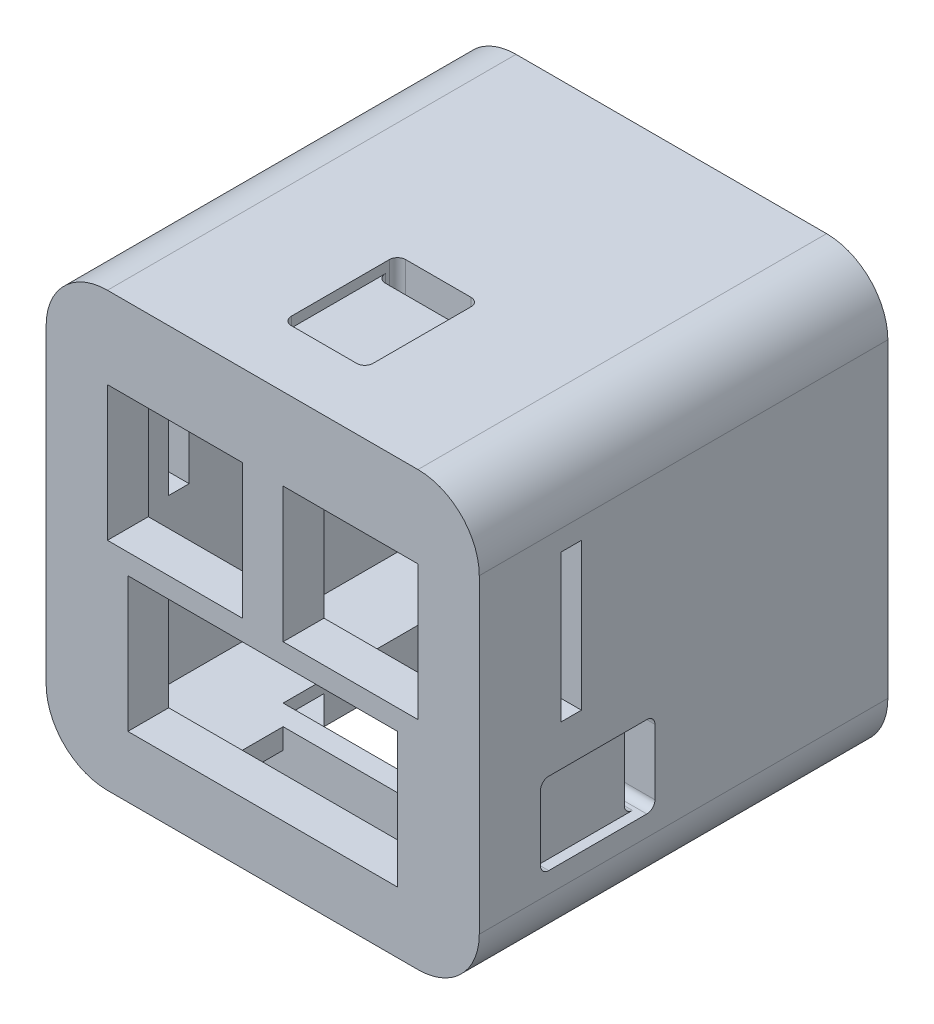
SolidWorks part; units mm, degrees
ref_plane "Front Plane" through (0, 0, 0) normal (0, 0, 1) x (1, 0, 0)
ref_plane "Top Plane" through (0, 0, 0) normal (0, 1, 0) x (1, 0, 0)
ref_plane "Right Plane" through (0, 0, 0) normal (1, 0, 0) x (0, 0, -1)
sketch "Sketch1" plane through (0, 0, 0) normal (0, 0, 1) x (1, 0, 0)
  line L1 (15, 0) -> (91, 0)
  line L2 (0, 15) -> (0, 91)
  line L3 (15, 106) -> (91, 106)
  line L4 (106, 15) -> (106, 91)
  line L5 (20, 15) -> (86, 15)
  line L6 (20, 15) -> (20, 48)
  line L7 (20, 48) -> (86, 48)
  line L8 (86, 15) -> (86, 48)
  line L9 (15, 86) -> (48, 86)
  line L10 (15, 86) -> (15, 53)
  line L11 (15, 53) -> (48, 53)
  line L12 (48, 86) -> (48, 53)
  line L13 (15, 86) -> (48, 53) construction
  line L14 (15, 53) -> (48, 86) construction
  line L19 (58, 86) -> (91, 86)
  line L20 (58, 86) -> (58, 53)
  line L21 (58, 53) -> (91, 53)
  line L22 (91, 86) -> (91, 53)
  line L23 (58, 86) -> (91, 53) construction
  line L24 (58, 53) -> (91, 86) construction
  arc A0 (91, 0) -> (106, 15) centre (91, 15) ccw
  arc A1 (0, 15) -> (15, 0) centre (15, 15) ccw
  arc A2 (15, 106) -> (0, 91) centre (15, 91) ccw
  arc A3 (91, 106) -> (106, 91) centre (91, 91) cw
  point P13 (106, 0)
  point P16 (0, 0)
  point P19 (0, 106)
  point P23 (87.3237, 87.1447)
  point P29 (31.5, 69.5)
  point P30 (74.5, 69.5)
  point P31 (0, 0)
  point P32 (53, 48)
  point P33 (53, 106)
  dimension "D7" = 15
  dimension "D1" = 66
  dimension "D2" = 33
  dimension "D3" = 10
  dimension "D4" = 5
  dimension "D5" = 33
  dimension "D6" = 33
  dimension "D8" = 33
  dimension "D9" = 33
  dimension "D10" = 15
  dimension "D11" = 15
  dimension "D12" = 20
  dimension "D13" = 15
extrude "Boss-Extrude1" add sketch "Sketch1" against normal blind 100
sketch "Sketch3" plane through (0, 0, -100) normal (0, 0, -1) x (-1, 0, 0)
  line L8 (-91, 106) -> (-15, 106) construction
  line L9 (-96, 96) -> (-10, 96)
  line L10 (-96, 96) -> (-96, 10)
  line L11 (-96, 10) -> (-10, 10)
  line L12 (-10, 96) -> (-10, 10)
  line L13 (-96, 96) -> (-10, 10) construction
  line L14 (-96, 10) -> (-10, 96) construction
  line L15 (0, 91) -> (0, 15) construction
  line L16 (-106, 15) -> (-106, 91) construction
  line L17 (-15, 0) -> (-91, 0) construction
  point P6 (-53, 53)
  dimension "D1" = 10
  dimension "D2" = 10
  dimension "D3" = 10
  dimension "D4" = 10
extrude "Cut-Extrude1" cut sketch "Sketch3" against normal offset from surface (90 mm away) 10 up to face at (31.5, 69.5, 0)
sketch "Sketch4" plane through (0, 106, 0) normal (0, 1, 0) x (1, 0, 0)
  line L0 (91, 100) -> (91, 0) construction
  line L1 (45, 43) -> (61, 43)
  line L2 (43, 41) -> (43, 17)
  line L3 (45, 15) -> (61, 15)
  line L4 (63, 41) -> (63, 17)
  line L5 (43, 43) -> (63, 15) construction
  line L6 (43, 15) -> (63, 43) construction
  line L8 (91, 0) -> (15, 0) construction
  arc A0 (63, 41) -> (61, 43) centre (61, 41) ccw
  arc A1 (63, 17) -> (61, 15) centre (61, 17) cw
  arc A2 (43, 17) -> (45, 15) centre (45, 17) ccw
  arc A3 (43, 41) -> (45, 43) centre (45, 41) cw
  point P4 (53, 29)
  dimension "D5" = 2
  dimension "D1" = 28
  dimension "D2" = 20
  dimension "D3" = 28
  dimension "D4" = 15
extrude "Cut-Extrude2" cut sketch "Sketch4" against normal blind 2.5
sketch "Sketch5" plane through (0, 103.5, 0) normal (0, 1, 0) x (1, 0, 0)
  line L0 (43, 41) -> (43, 17) construction
  line L1 (45, 38) -> (61, 38)
  line L2 (43, 40) -> (43, 41)
  line L3 (45, 43) -> (61, 43)
  line L4 (63, 40) -> (63, 41)
  line L5 (43, 38) -> (63, 43) construction
  line L6 (43, 43) -> (63, 38) construction
  line L8 (63, 17) -> (63, 41) construction
  line L9 (61, 43) -> (45, 43) construction
  arc A0 (61, 43) -> (63, 41) centre (61, 41) cw
  arc A1 (63, 40) -> (61, 38) centre (61, 40) cw
  arc A2 (43, 40) -> (45, 38) centre (45, 40) ccw
  arc A3 (43, 41) -> (45, 43) centre (45, 41) cw
  point P4 (53, 40.5)
  dimension "D2" = 2
  dimension "D1" = 5
extrude "Cut-Extrude3" cut sketch "Sketch5" against normal blind 18.5
ref_plane "Plane1" through (0, 0, -20) normal (0, 0, 1) x (1, 0, 0)
sketch "Sketch6" plane through (0, 0, -20) normal (0, 0, 1) x (1, 0, 0)
  line L1 (111.7264, 86) -> (-8.745, 86)
  line L2 (111.7264, 86) -> (111.7264, 50)
  line L3 (111.7264, 50) -> (-8.745, 50)
  line L4 (-8.745, 86) -> (-8.745, 50)
  line L5 (111.7264, 86) -> (-8.745, 50) construction
  line L6 (111.7264, 50) -> (-8.745, 86) construction
  line L11 (91, 106) -> (15, 106) construction
  point P4 (51.4907, 68)
  dimension "D8" = 36
  dimension "D9" = 20
extrude "Cut-Extrude4" cut sketch "Sketch6" against normal blind 5 contours L2 L3 L4 L1
sketch "Sketch7" plane through (106, 0, 0) normal (1, 0, 0) x (0, 0, -1)
  line L0 (0, 15) -> (0, 91) construction
  line L1 (17, 40) -> (41, 40)
  line L2 (15, 38) -> (15, 22)
  line L3 (17, 20) -> (41, 20)
  line L4 (43, 38) -> (43, 22)
  line L5 (15, 40) -> (43, 20) construction
  line L6 (15, 20) -> (43, 40) construction
  line L7 (25, 50) -> (20, 50) construction
  arc A0 (15, 38) -> (17, 40) centre (17, 38) cw
  arc A1 (15, 22) -> (17, 20) centre (17, 22) ccw
  arc A2 (41, 20) -> (43, 22) centre (41, 22) ccw
  arc A3 (43, 38) -> (41, 40) centre (41, 38) ccw
  point P4 (29, 30)
  dimension "D5" = 2
  dimension "D1" = 28
  dimension "D2" = 20
  dimension "D3" = 15
  dimension "D4" = 10
extrude "Cut-Extrude5" cut sketch "Sketch7" against normal blind 2.5
sketch "Sketch8" plane through (103.5, 0, 0) normal (1, 0, 0) x (0, 0, -1)
  line L0 (41, 40) -> (17, 40) construction
  line L1 (40, 40) -> (41, 40)
  line L2 (38, 38) -> (38, 22)
  line L3 (40, 20) -> (41, 20)
  line L4 (43, 38) -> (43, 22)
  line L5 (38, 40) -> (43, 20) construction
  line L6 (38, 20) -> (43, 40) construction
  line L7 (43, 22) -> (43, 38) construction
  line L8 (17, 20) -> (41, 20) construction
  arc A0 (40, 20) -> (38, 22) centre (40, 22) cw
  arc A1 (41, 20) -> (43, 22) centre (41, 22) ccw
  arc A2 (43, 38) -> (41, 40) centre (41, 38) ccw
  arc A3 (40, 40) -> (38, 38) centre (40, 38) ccw
  point P4 (40.5, 30)
  dimension "D2" = 2
  dimension "D1" = 5
extrude "Cut-Extrude6" cut sketch "Sketch8" against normal blind 10
ref_plane "Plane2" through (53, 0, 0) normal (1, 0, 0) x (0, 0, -1)
mirror "Mirror1" about plane through (53, 0, 0) normal (1, 0, 0) of "Cut-Extrude6", "Cut-Extrude5"
sketch "Sketch9" plane through (0, 0, 0) normal (0, -1, 0) x (1, 0, 0)
  line L0 (15, 0) -> (91, 0) construction
  line L1 (23, -15) -> (83, -15)
  line L2 (23, -15) -> (23, -25)
  line L3 (23, -25) -> (83, -25)
  line L4 (83, -15) -> (83, -25)
  line L5 (23, -15) -> (83, -25) construction
  line L6 (23, -25) -> (83, -15) construction
  line L7 (23, -85) -> (83, -85)
  line L8 (23, -85) -> (23, -95)
  line L9 (23, -95) -> (83, -95)
  line L10 (83, -85) -> (83, -95)
  line L11 (23, -85) -> (83, -95) construction
  line L12 (23, -95) -> (83, -85) construction
  line L13 (15, -100) -> (91, -100) construction
  line L14 (91, -100) -> (91, 0) construction
  point P4 (53, -20)
  point P9 (53, -90)
  dimension "D1" = 10
  dimension "D2" = 10
  dimension "D3" = 15
  dimension "D4" = 5
  dimension "D5" = 60
  dimension "D6" = 60
  dimension "D7" = 8
  dimension "D8" = 8
extrude "Cut-Extrude7" cut sketch "Sketch9" against normal blind 5
sketch "Sketch10" plane through (0, 5, 0) normal (0, -1, 0) x (1, 0, 0)
  line L0 (83, -15) -> (23, -15) construction
  line L1 (33, -15) -> (73, -15)
  line L2 (33, -15) -> (33, -25)
  line L3 (33, -25) -> (73, -25)
  line L4 (73, -15) -> (73, -25)
  line L5 (33, -15) -> (73, -25) construction
  line L6 (33, -25) -> (73, -15) construction
  line L7 (23, -25) -> (83, -25) construction
  line L8 (83, -85) -> (23, -85) construction
  line L9 (33, -85) -> (73, -85)
  line L10 (33, -85) -> (33, -95)
  line L11 (33, -95) -> (73, -95)
  line L12 (73, -85) -> (73, -95)
  line L13 (33, -85) -> (73, -95) construction
  line L14 (33, -95) -> (73, -85) construction
  line L15 (23, -95) -> (83, -95) construction
  line L16 (23, -15) -> (23, -25) construction
  line L17 (83, -25) -> (83, -15) construction
  line L18 (83, -95) -> (83, -85) construction
  line L19 (23, -85) -> (23, -95) construction
  point P4 (53, -20)
  point P13 (53, -90)
  dimension "D1" = 10
  dimension "D2" = 10
  dimension "D3" = 10
  dimension "D4" = 10
extrude "Cut-Extrude8" cut sketch "Sketch10" against normal blind 5
sketch "Sketch11" plane through (0, 10, 0) normal (0, 1, 0) x (1, 0, 0)
  line L0 (91, 100) -> (15, 100) construction
  line L1 (28, 80) -> (78, 80)
  line L2 (28, 80) -> (28, 30)
  line L3 (28, 30) -> (78, 30)
  line L4 (78, 80) -> (78, 30)
  line L5 (28, 80) -> (78, 30) construction
  line L6 (28, 30) -> (78, 80) construction
  point P4 (53, 55)
  point P5 (53, 80)
  point P6 (53, 100)
  point P7 (0, 0)
  point P13 (0, 0)
  point P14 (0, 0)
  point P15 (0, 0)
  dimension "D1" = 50
  dimension "D2" = 50
extrude "Cut-Extrude11" cut sketch "Sketch11" against normal blind 3
sketch "Sketch12" plane through (0, 7, 0) normal (0, 1, 0) x (1, 0, 0)
  line L0 (38, 80) -> (68, 80)
  line L1 (68, 80) -> (78, 70)
  line L2 (78, 70) -> (78, 40)
  line L3 (78, 40) -> (68, 30)
  line L4 (68, 30) -> (38, 30)
  line L5 (38, 30) -> (28, 40)
  line L6 (28, 40) -> (28, 70)
  line L7 (28, 70) -> (38, 80)
  line L8 (91, 100) -> (15, 100) construction
  point P2 (53, 80)
  point P11 (53, 100)
  dimension "D1" = 50
  dimension "D2" = 50
  dimension "D3" = 30
  dimension "D4" = 30
  dimension "D5" = 30
  dimension "D6" = 30
  dimension "D7" = 20
extrude "Cut-Extrude12" cut sketch "Sketch12" against normal blind 10
